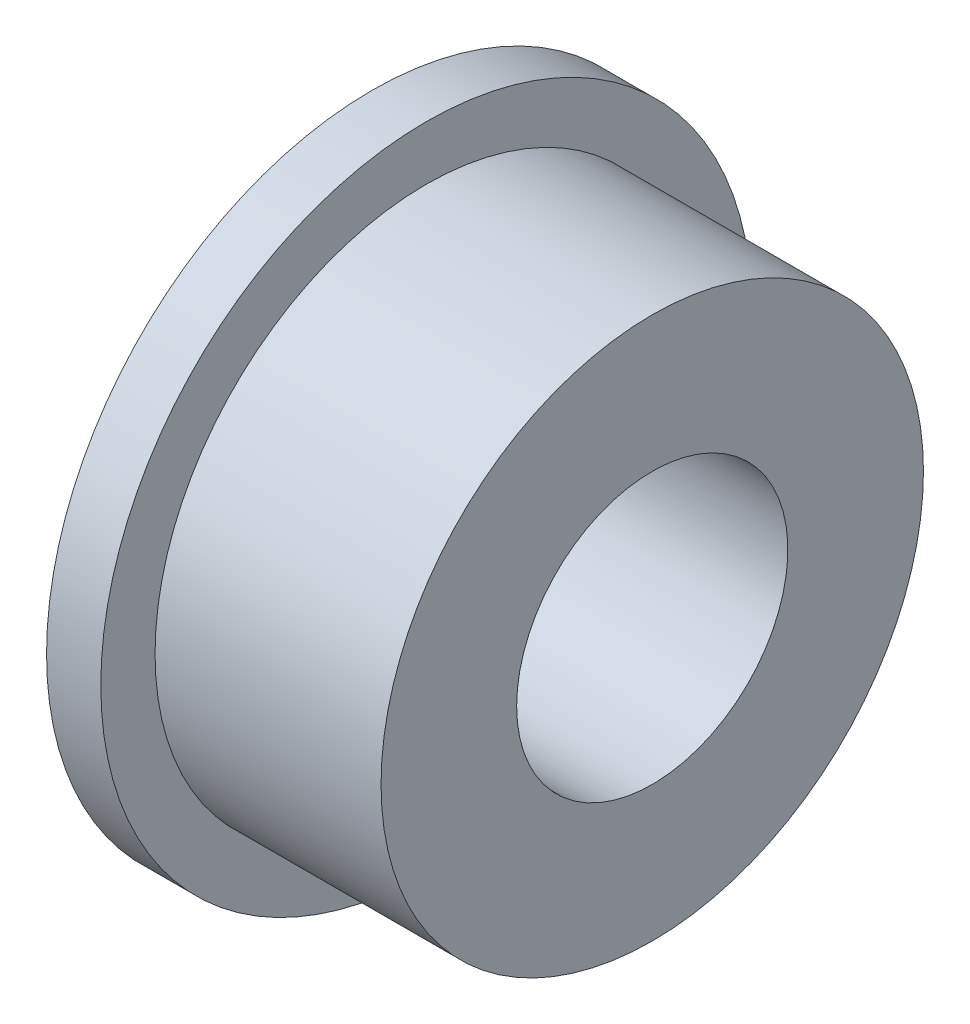
SolidWorks part; units mm, degrees
ref_plane "Front Plane" through (0, 0, 0) normal (0, 0, 1) x (1, 0, 0)
ref_plane "Top Plane" through (0, 0, 0) normal (0, 1, 0) x (1, 0, 0)
ref_plane "Right Plane" through (0, 0, 0) normal (1, 0, 0) x (0, 0, -1)
sketch "Sketch1" plane through (0, 0, 0) normal (0, 0, 1) x (1, 0, 0)
  line L0 (0, 0) -> (16.6026, 0) construction
  line L1 (0, 1.5) -> (0, 3.6)
  line L2 (0, 3.6) -> (0.6, 3.6)
  line L3 (0.6, 3.6) -> (0.6, 3)
  line L4 (0.6, 3) -> (3.1, 3)
  line L5 (3.1, 3) -> (3.1, 1.5)
  line L6 (3.1, 1.5) -> (0, 1.5)
  dimension "D1" = 1.5
  dimension "D2" = 3
  dimension "D3" = 3.6
  dimension "D4" = 0.6
  dimension "D5" = 2.5
revolve "Revolve1" add sketch "Sketch1" angle 360 about L0
